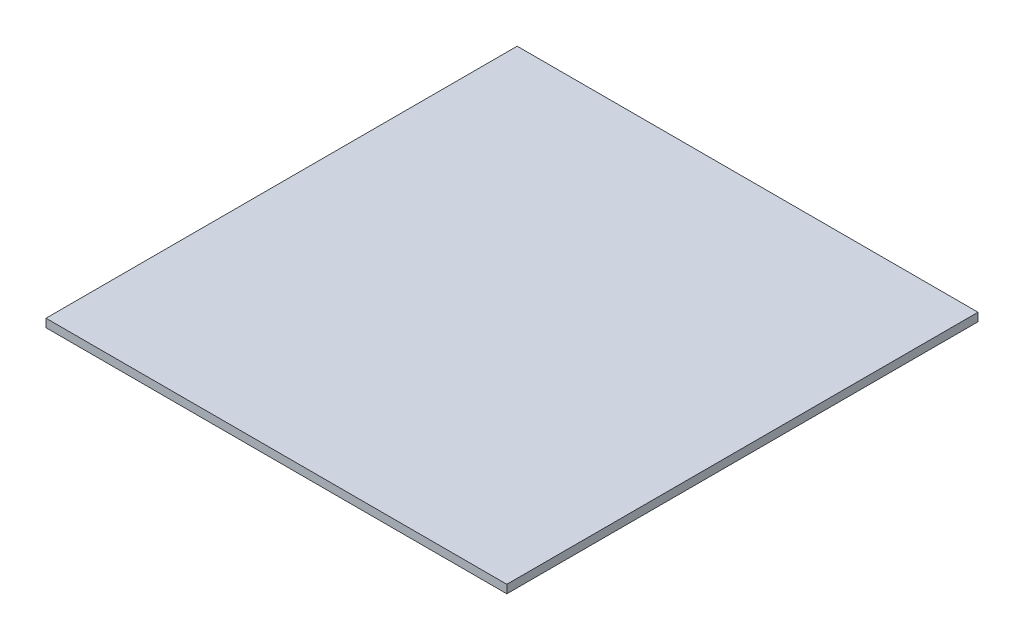
SolidWorks part; units mm, degrees
ref_plane "Front Plane" through (0, 0, 0) normal (0, 0, 1) x (1, 0, 0)
ref_plane "Top Plane" through (0, 0, 0) normal (0, 1, 0) x (1, 0, 0)
ref_plane "Right Plane" through (0, 0, 0) normal (1, 0, 0) x (0, 0, -1)
sketch "Sketch2" plane through (0, 0, 0) normal (0, 1, 0) x (1, 0, 0)
  line L1 (0, 0) -> (445, 0)
  line L2 (0, 0) -> (0, 455)
  line L3 (0, 455) -> (445, 455)
  line L4 (445, 0) -> (445, 455)
  dimension "D1" = 445
  dimension "D2" = 455
extrude "Boss-Extrude1" add sketch "Sketch2" along normal blind 8
